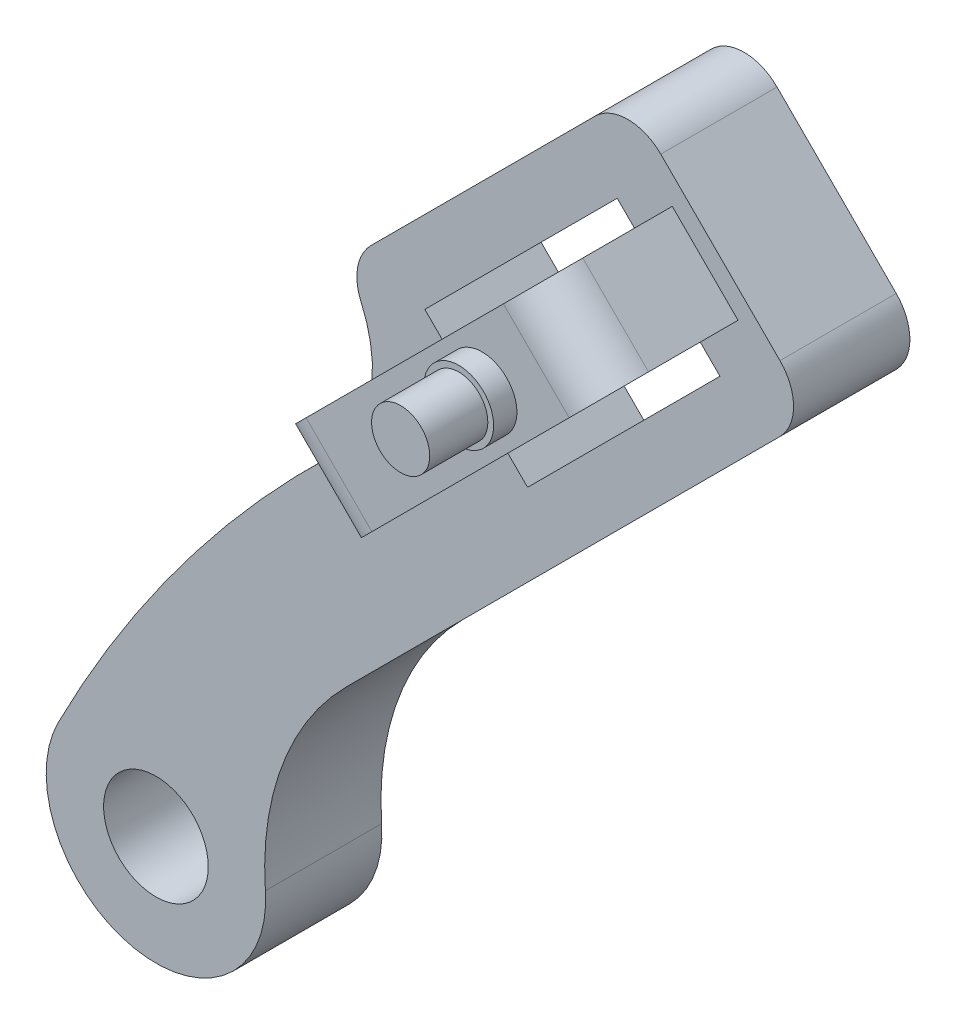
SolidWorks part; units mm, degrees
ref_plane "前视基准面" through (0, 0, 0) normal (0, 0, 1) x (1, 0, 0)
ref_plane "上视基准面" through (0, 0, 0) normal (0, 1, 0) x (1, 0, 0)
ref_plane "右视基准面" through (0, 0, 0) normal (1, 0, 0) x (0, 0, -1)
sketch "草图2" plane through (0, 0, 0) normal (0, 0, 1) x (1, 0, 0)
  line L0 (39.2294, 23.5816) -> (22.6831, 7.0353)
  line L1 (39.2294, 23.5816) -> (30.3905, 32.4204)
  line L2 (22.6831, 7.0353) -> (13.8442, 15.8741)
  line L3 (30.3905, 32.4204) -> (13.8442, 15.8741)
  line L4 (0, 0) -> (49.6838, 0) construction
  line L5 (0, 0) -> (0, -28.803) construction
  line L6 (7.1022, -15.6167) -> (44.3912, 21.6724)
  line L7 (44.3912, 27.3292) -> (34.1382, 37.5823)
  line L8 (28.4813, 37.5823) -> (9.2154, 18.3163)
  arc A0 (9.2154, 18.3163) -> (8.3621, 13.6812) centre (12.1521, 15.3796) ccw
  arc A1 (8.3621, 13.6812) -> (5.8862, 1.001) centre (-1.8675, 9.0968) cw
  arc A2 (-17.6852, -30.6634) -> (0.1294, -34.2938) centre (-9.2839, -34.9612) ccw
  arc A3 (0.1294, -34.2938) -> (7.1022, -15.6167) centre (24.0811, -32.5956) cw
  arc A4 (5.8862, 1.001) -> (-17.6852, -30.6634) centre (87.9841, -84.7194) ccw
  circle A5 centre (-9.2839, -34.9612) radius 4.5
  arc A6 (44.3912, 21.6724) -> (44.3912, 27.3292) centre (41.5628, 24.5008) ccw
  arc A7 (34.1382, 37.5823) -> (28.4813, 37.5823) centre (31.3098, 34.7539) ccw
  dimension "D7" = 82
  dimension "D8" = 9
  dimension "D9" = 4
  dimension "D1" = 12.5
  dimension "D2" = 23.4
  dimension "D3" = 5
  dimension "D4" = 6.3
  dimension "D5" = 5
  dimension "D6" = 45
extrude "凸台-拉伸1" add sketch "草图2" along normal blind 10
ref_plane "基准面1" through (3.2984, -3.2984, 0) normal (0.7071, -0.7071, 0) x (0, 0, -1)
sketch "草图4" plane through (3.2984, -3.2984, 0) normal (0.7071, -0.7071, 0) x (0, 0, -1)
  line L16 (-9.6974, 20.014) -> (-9.6974, 17.014)
  line L17 (-9.6974, 46.014) -> (-9.6974, 49.014)
  line L19 (-17.6974, 17.014) -> (-9.6974, 17.014)
  line L20 (-21.6974, 45.014) -> (-21.6974, 21.014)
  line L21 (-9.6974, 49.014) -> (-17.6974, 49.014)
  line L22 (-16.6974, 20.014) -> (-9.6974, 20.014)
  line L23 (-16.6974, 46.014) -> (-16.6974, 20.014)
  line L24 (-9.6974, 46.014) -> (-16.6974, 46.014)
  arc A2 (-17.6974, 49.014) -> (-21.6974, 45.014) centre (-17.6974, 45.014) ccw
  arc A3 (-21.6974, 21.014) -> (-17.6974, 17.014) centre (-17.6974, 21.014) ccw
extrude "凸台-拉伸2" add sketch "草图4" along normal mid plane 8
sketch "草图12" plane through (0, 0, 0) normal (0, 0, -1) x (-1, 0, 0)
  line L0 (-13.8442, 15.8741) -> (-22.6831, 7.0353) construction
  line L2 (-30.3905, 32.4204) -> (-13.8442, 15.8741) construction
  line L4 (-39.2294, 23.5816) -> (-30.3905, 32.4204) construction
  circle A0 centre (-16.3545, 9.7576) radius 0.8
  circle A1 centre (-36.507, 29.9102) radius 0.8
  dimension "D3" = 1.6
  dimension "D6" = 1.6
  dimension "D1" = 2.55
  dimension "D2" = 6.1
  dimension "D4" = 6.1
  dimension "D5" = 2.55
extrude "切除-拉伸2" cut sketch "草图12" against normal blind 8
sketch "草图13" plane through (0, 0, 21.6974) normal (0, 0, 1) x (1, 0, 0)
  line L0 (37.9566, 25.7029) -> (20.986, 8.7323) construction
  line L1 (37.9566, 25.7029) -> (32.2997, 31.3598) construction
  circle A0 centre (30.4612, 23.8644) radius 3
  dimension "D3" = 6
  dimension "D1" = 4
  dimension "D2" = 6.6
extrude "凸台-拉伸3" add sketch "草图13" along normal blind 2
sketch "草图19" plane through (0, 0, 23.6974) normal (0, 0, 1) x (1, 0, 0)
  circle A1 centre (30.4612, 23.8644) radius 2.5
extrude "凸台-拉伸5" add sketch "草图19" along normal blind 5 contours A1
